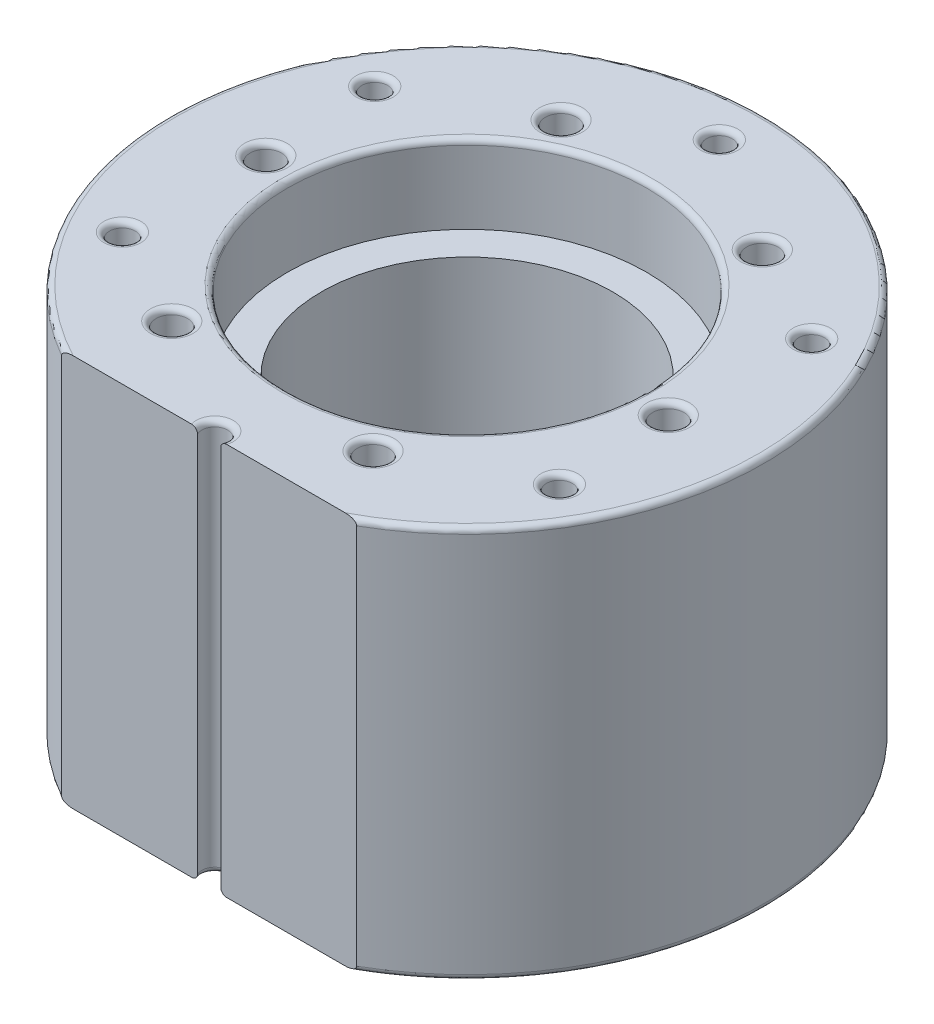
SolidWorks part; units mm, degrees
ref_plane "Front Plane" through (0, 0, 0) normal (0, 0, 1) x (1, 0, 0)
ref_plane "Top Plane" through (0, 0, 0) normal (0, 1, 0) x (1, 0, 0)
ref_plane "Right Plane" through (0, 0, 0) normal (1, 0, 0) x (0, 0, -1)
sketch "Sketch1" plane through (0, 0, 0) normal (0, 0, 1) x (1, 0, 0)
  line L0 (0, 0) -> (0, 13.3508) construction
  line L1 (16.025, 35) -> (26.5, 35)
  line L2 (26.5, 35) -> (26.5, 0)
  line L3 (26.5, 0) -> (13, 0)
  line L4 (16.025, 35) -> (16.025, 28)
  line L5 (16.025, 28) -> (13, 28)
  line L6 (13, 28) -> (13, 0)
  dimension "D1" = 53
  dimension "D2" = 32.05
  dimension "D3" = 26
  dimension "D4" = 35
  dimension "D5" = 7
revolve "Revolve1" add sketch "Sketch1" angle 360 about L0
sketch "Sketch2" plane through (0, 35, 0) normal (0, 1, 0) x (1, 0, 0)
  circle A2 centre (-8.5905, 16.9751) radius 1.4
  circle A3 centre (10.4056, 15.9271) radius 1.4
  circle A4 centre (18.9961, -1.048) radius 1.4
  circle A5 centre (8.5905, -16.9751) radius 1.4
  circle A6 centre (-10.4056, -15.9271) radius 1.4
  circle A7 centre (-18.9961, 1.048) radius 1.4
  circle A8 centre (0, 0) radius 19.025 construction
  circle A9 centre (-8.5905, 16.9751) radius 1.6 construction
  circle A10 centre (-8.5905, 16.9751) radius 1.6 construction
  point P16 (0, 0)
  point P17 (0, 0)
  point P18 (0, 0)
  dimension "D1" = 2.8
  dimension "D2" = 6
extrude "Cut-Extrude1" cut sketch "Sketch2" against normal blind 20
sketch "Sketch4" plane through (0, 0, 0) normal (0, -1, 0) x (1, 0, 0)
  circle A0 centre (0, 0) radius 22.5 construction
  circle A1 centre (0, 22.5) radius 1.15
  circle A2 centre (19.4856, 11.25) radius 1.15
  circle A3 centre (19.4856, -11.25) radius 1.15
  circle A4 centre (0, -22.5) radius 1.15
  circle A5 centre (-19.4856, -11.25) radius 1.15
  circle A6 centre (-19.4856, 11.25) radius 1.15
  point P17 (0, 0)
  dimension "D1" = 45
  dimension "D2" = 2.3
  dimension "D3" = 6
extrude "Cut-Extrude2" cut sketch "Sketch4" against normal through all
fillet "Fillet1" radius 0.5 22 edges at (0, 0, -13) (0, 0, -26.5) (19.4856, 0, 10.1) (19.4856, 0, -12.4) (0, 0, -23.65) (-19.4856, 0, -12.4) (-19.4856, 0, 10.1) (0, 0, 21.35) (0, 35, -26.5) (0, 35, -16.025) (-8.5905, 35, -15.5751) (10.4056, 35, -14.5271) (18.9961, 35, 2.448) (8.5905, 35, 18.3751) (-10.4056, 35, 17.3271) (-18.9961, 35, 0.352) (19.4856, 35, 10.1) (19.4856, 35, -12.4) (0, 35, -23.65) (-19.4856, 35, -12.4) (-19.4856, 35, 10.1) (0, 35, 21.35)
sketch "Sketch6" plane through (0, 35, 0) normal (0, 1, 0) x (1, 0, 0)
  line L1 (61.3311, -32.6332) -> (-59.7715, -32.6332)
  line L2 (61.3311, -32.6332) -> (61.3311, -23)
  line L3 (61.3311, -23) -> (-59.7715, -23)
  line L4 (-59.7715, -32.6332) -> (-59.7715, -23)
  dimension "D1" = 23
extrude "Cut-Extrude3" cut sketch "Sketch6" against normal through all
